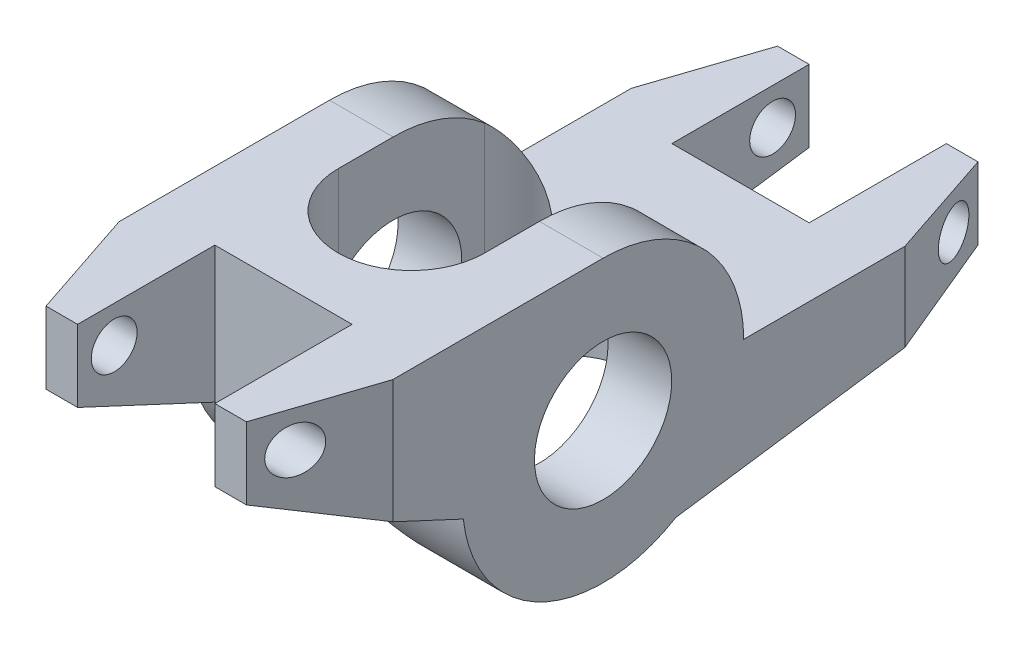
SolidWorks part; units mm, degrees
ref_plane "Front Plane" through (0, 0, 0) normal (0, 0, 1) x (1, 0, 0)
ref_plane "Top Plane" through (0, 0, 0) normal (0, 1, 0) x (1, 0, 0)
ref_plane "Right Plane" through (0, 0, 0) normal (1, 0, 0) x (0, 0, -1)
sketch "Sketch1" plane through (0, 0, 0) normal (1, 0, 0) x (0, 0, -1)
  line L0 (0, 9.765) -> (-22.225, 9.765)
  line L1 (-22.225, 9.765) -> (-22.225, 4.765)
  line L2 (-22.225, 4.765) -> (-9.7059, -1.0728)
  line L3 (9.765, 0) -> (28.575, 0)
  line L4 (28.575, 0) -> (28.575, -5)
  line L5 (28.575, -5) -> (5.0532, -8.3558)
  circle A0 centre (0, 0) radius 4.765
  arc A1 (-9.7059, -1.0728) -> (5.0532, -8.3558) centre (0, 0) ccw
  circle A2 centre (0, 0) radius 9.765 construction
  arc A3 (9.765, 0) -> (0, 9.765) centre (0, 0) ccw
  dimension "D1" = 9.53
  dimension "D3" = 5
  dimension "D4" = 22.225
  dimension "D5" = 25
  dimension "D6" = 5
  dimension "D7" = 28.575
  dimension "D2" = 5
extrude "Boss-Extrude1" add sketch "Sketch1" along normal mid plane 19
chamfer "Chamfer1" distance 2.54 distance2 7.62 2 edges at (9.5, -2.5, -28.575) (9.5, 7.265, 22.225)
chamfer "Chamfer2" distance 7.62 distance2 2.54 2 edges at (-9.5, -2.5, -28.575) (-9.5, 7.265, 22.225)
sketch "Sketch2" plane through (0, 0, 0) normal (0, 1, 0) x (1, 0, 0)
  line L0 (0, -3.81) -> (0, 6.35) construction
  line L1 (-5.08, -3.81) -> (-5.08, 6.35)
  line L2 (5.08, -3.81) -> (5.08, 6.35)
  arc A0 (-5.08, -3.81) -> (5.08, -3.81) centre (0, -3.81) ccw
  arc A1 (5.08, 6.35) -> (-5.08, 6.35) centre (0, 6.35) ccw
  point P3 (0, 1.27)
  dimension "D1" = 10.16
  dimension "D2" = 10.16
  dimension "D3" = 3.81
extrude "Cut-Extrude1" cut sketch "Sketch2" against normal mid plane 35
sketch "Sketch3" plane through (0, 0, 0) normal (0, 1, 0) x (1, 0, 0)
  line L0 (6.96, 28.575) -> (-6.96, 28.575) construction
  line L1 (-4.765, 19.045) -> (4.765, 19.045)
  line L2 (-4.765, 19.045) -> (-4.765, 28.575)
  line L3 (-4.765, 28.575) -> (4.765, 28.575)
  line L4 (4.765, 19.045) -> (4.765, 28.575)
  line L5 (-4.765, 19.045) -> (4.765, 28.575) construction
  line L6 (-4.765, 28.575) -> (4.765, 19.045) construction
  line L7 (6.96, -22.225) -> (-6.96, -22.225) construction
  line L8 (-4.765, -12.695) -> (4.765, -12.695)
  line L9 (-4.765, -12.695) -> (-4.765, -22.225)
  line L10 (-4.765, -22.225) -> (4.765, -22.225)
  line L11 (4.765, -12.695) -> (4.765, -22.225)
  line L12 (-4.765, -12.695) -> (4.765, -22.225) construction
  line L13 (-4.765, -22.225) -> (4.765, -12.695) construction
  point P0 (0, 23.81)
  point P7 (0, -17.46)
  dimension "D1" = 9.53
  dimension "D2" = 9.53
  dimension "D3" = 9.53
  dimension "D4" = 9.53
extrude "Cut-Extrude2" cut sketch "Sketch3" against normal mid plane 35
sketch "Sketch4" plane through (0, 0, 0) normal (1, 0, 0) x (0, 0, -1)
  line L0 (20.955, 0) -> (28.575, 0) construction
  line L1 (28.575, 0) -> (28.575, -5) construction
  line L2 (-22.225, 9.765) -> (-14.605, 9.765) construction
  line L3 (-22.225, 4.765) -> (-22.225, 9.765) construction
  circle A0 centre (26.035, -2.54) radius 1.59
  circle A1 centre (-19.685, 7.225) radius 1.59
  dimension "D1" = 3.18
  dimension "D2" = 2.54
  dimension "D3" = 2.54
  dimension "D4" = 2.54
  dimension "D5" = 2.54
extrude "Cut-Extrude3" cut sketch "Sketch4" against normal mid plane 35
